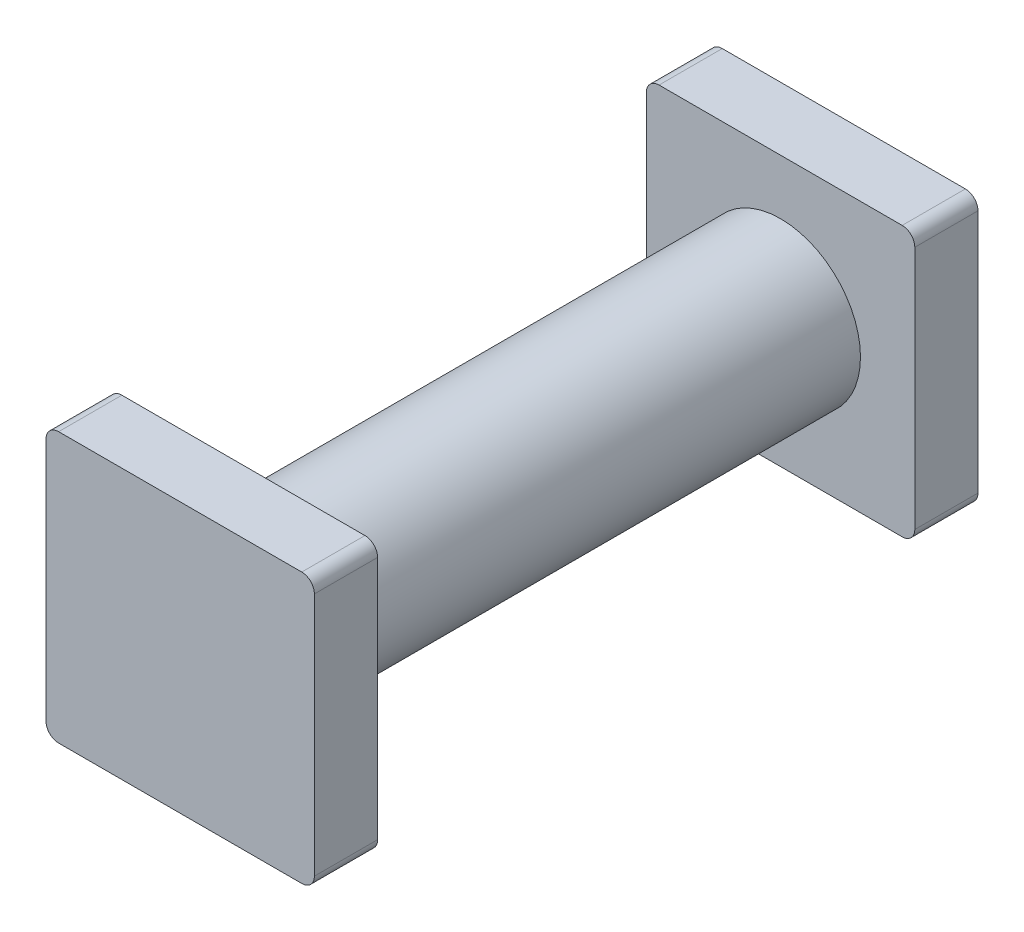
SolidWorks part; units mm, degrees
material "2024-T361"
ref_plane "Front Plane" through (0, 0, 0) normal (0, 0, 1) x (1, 0, 0)
ref_plane "Top Plane" through (0, 0, 0) normal (0, 1, 0) x (1, 0, 0)
ref_plane "Right Plane" through (0, 0, 0) normal (1, 0, 0) x (0, 0, -1)
sketch "Sketch1" plane through (0, 0, 0) normal (0, 0, 1) x (1, 0, 0)
  line L0 (-229.5784, -284.382) -> (40.4216, -284.382) construction
  line L1 (-229.5784, -445.7672) -> (-229.5784, 54.2328) construction
  line L2 (40.4216, -445.7672) -> (40.4216, 54.2328) construction
  line L3 (40.4216, -284.382) -> (-94.5784, -284.382) construction
  line L5 (-115.8121, -305.7192) -> (-73.3448, -305.7192)
  line L6 (-115.8121, -305.7192) -> (-115.8121, -263.0448)
  line L7 (-115.8121, -263.0448) -> (-73.3448, -263.0448)
  line L8 (-73.3448, -305.7192) -> (-73.3448, -263.0448)
  line L9 (-115.8121, -305.7192) -> (-73.3448, -263.0448) construction
  line L10 (-115.8121, -263.0448) -> (-73.3448, -305.7192) construction
extrude "Boss-Extrude1" add sketch "Sketch1" along normal blind 10
sketch "Sketch2" plane through (0, 0, 10) normal (0, 0, 1) x (1, 0, 0)
  line L0 (-115.8121, -284.382) -> (-73.3448, -284.382) construction
  line L1 (-115.8121, -263.0448) -> (-115.8121, -305.7192) construction
  line L2 (-73.3448, -305.7192) -> (-73.3448, -263.0448) construction
  line L3 (-73.3448, -284.382) -> (-94.5784, -284.382) construction
  circle A0 centre (-94.5784, -284.382) radius 12.6374
extrude "Boss-Extrude2" add sketch "Sketch2" along normal blind 89
sketch "Sketch4" plane through (0, 0, 105) normal (0, 0, -1) x (-1, 0, 0)
  line L0 (94.5784, -305.7192) -> (94.5784, -263.0448) construction
  line L1 (115.8121, -305.7192) -> (73.3448, -305.7192) construction
  line L2 (73.3448, -263.0448) -> (115.8121, -263.0448) construction
  line L3 (94.5784, -263.0448) -> (94.5784, -284.382) construction
  line L5 (115.8121, -305.7192) -> (73.3448, -305.7192)
  line L6 (115.8121, -305.7192) -> (115.8121, -263.0448)
  line L7 (115.8121, -263.0448) -> (73.3448, -263.0448)
  line L8 (73.3448, -305.7192) -> (73.3448, -263.0448)
  line L9 (115.8121, -305.7192) -> (73.3448, -263.0448) construction
  line L10 (115.8121, -263.0448) -> (73.3448, -305.7192) construction
extrude "Boss-Extrude3" add sketch "Sketch4" along normal blind 10
fillet "Fillet1" radius 2 8 edges at (-73.3448, -263.0448, 5) (-73.3448, -263.0448, 100) (-73.3448, -305.7192, 100) (-73.3448, -305.7192, 5) (-115.8121, -305.7192, 5) (-115.8121, -263.0448, 5) (-115.8121, -263.0448, 100) (-115.8121, -305.7192, 100)
